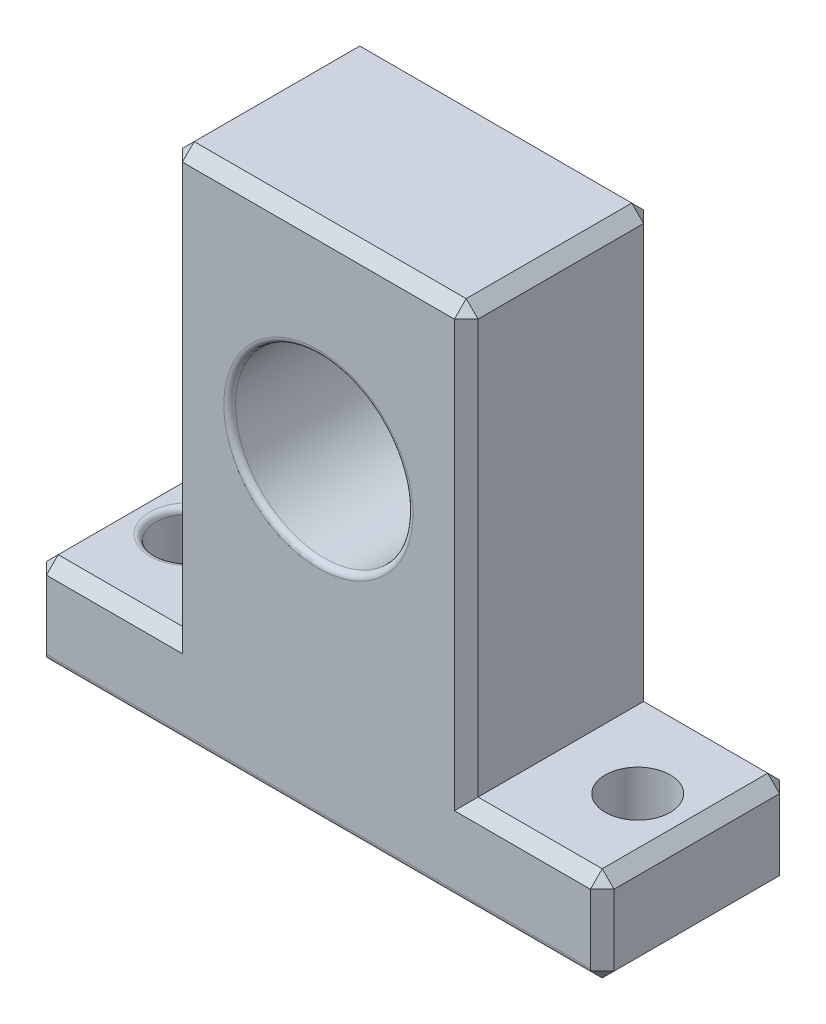
SolidWorks part; units mm, degrees
ref_plane "前视基准面" through (0, 0, 0) normal (0, 0, 1) x (1, 0, 0)
ref_plane "上视基准面" through (0, 0, 0) normal (0, 1, 0) x (1, 0, 0)
ref_plane "右视基准面" through (0, 0, 0) normal (1, 0, 0) x (0, 0, -1)
other "Configuration Table"
sketch "草图1" plane through (0, 0, 0) normal (0, 1, 0) x (1, 0, 0)
  line L1 (24, -8) -> (-24, -8)
  line L2 (24, -8) -> (24, 8)
  line L3 (24, 8) -> (-24, 8)
  line L4 (-24, -8) -> (-24, 8)
  line L5 (24, -8) -> (-24, 8) construction
  line L6 (24, 8) -> (-24, -8) construction
  circle A0 centre (19, 0) radius 2.75
  circle A1 centre (-19, 0) radius 2.75
  point P0 (0, 0)
  dimension "D3" = 5.5
  dimension "D4" = 5.5
  dimension "D5" = 38
  dimension "D6" = 19
  dimension "D1" = 48
  dimension "D2" = 16
extrude "凸台-拉伸1" add sketch "草图1" along normal blind 8
sketch "草图2" plane through (0, 8, 0) normal (0, 1, 0) x (1, 0, 0)
  line L0 (12.5, 8) -> (12.5, -8)
  line L1 (-12.5, 8) -> (-12.5, -8)
  line L7 (-12.5, 8) -> (12.5, 8)
  line L12 (-12.5, -8) -> (12.5, -8)
  line L13 (-12.5, 8) -> (12.5, -8)
  point P0 (0, 0)
  line M9 (-24, -8) -> (24, -8)
  line M11 (24, 8) -> (-24, 8)
  dimension "D2" = 25
  dimension "D1" = 16
extrude "凸台-拉伸2" add sketch "草图2" along normal blind 36 contours L13 L0 M11 | L13 L1 M9
sketch "草图3" plane through (0, 0, 8) normal (0, 0, 1) x (1, 0, 0)
  line L0 (0, 27) -> (0, 0) construction
  circle A0 centre (0, 27) radius 7.5
  dimension "D1" = 27
  dimension "D2" = 15
extrude "切除-拉伸1" cut sketch "草图3" against normal blind 36
chamfer "倒角1" distance 1 angle 45 22 edges at (0, 44, -8) (0, 44, 8) (12.5, 44, 0) (-12.5, 26, 8) (-12.5, 44, 0) (-12.5, 26, -8) (0, 0, -8) (-18.25, 8, -8) (-18.25, 8, 8) (-24, 0, 0) (-24, 4, -8) (-24, 8, 0) (-24, 4, 8) (0, 0, 8) (24, 4, 8) (24, 0, 0) (24, 4, -8) (12.5, 26, -8) (12.5, 26, 8) (18.25, 8, -8) (24, 8, 0) (18.25, 8, 8)
fillet "圆角1" radius 0.5 5 edges at (7.5, 27, -8) (7.5, 27, 8) (-19, 0, 2.75) (-19, 8, 2.75) (0, 1, 8)
